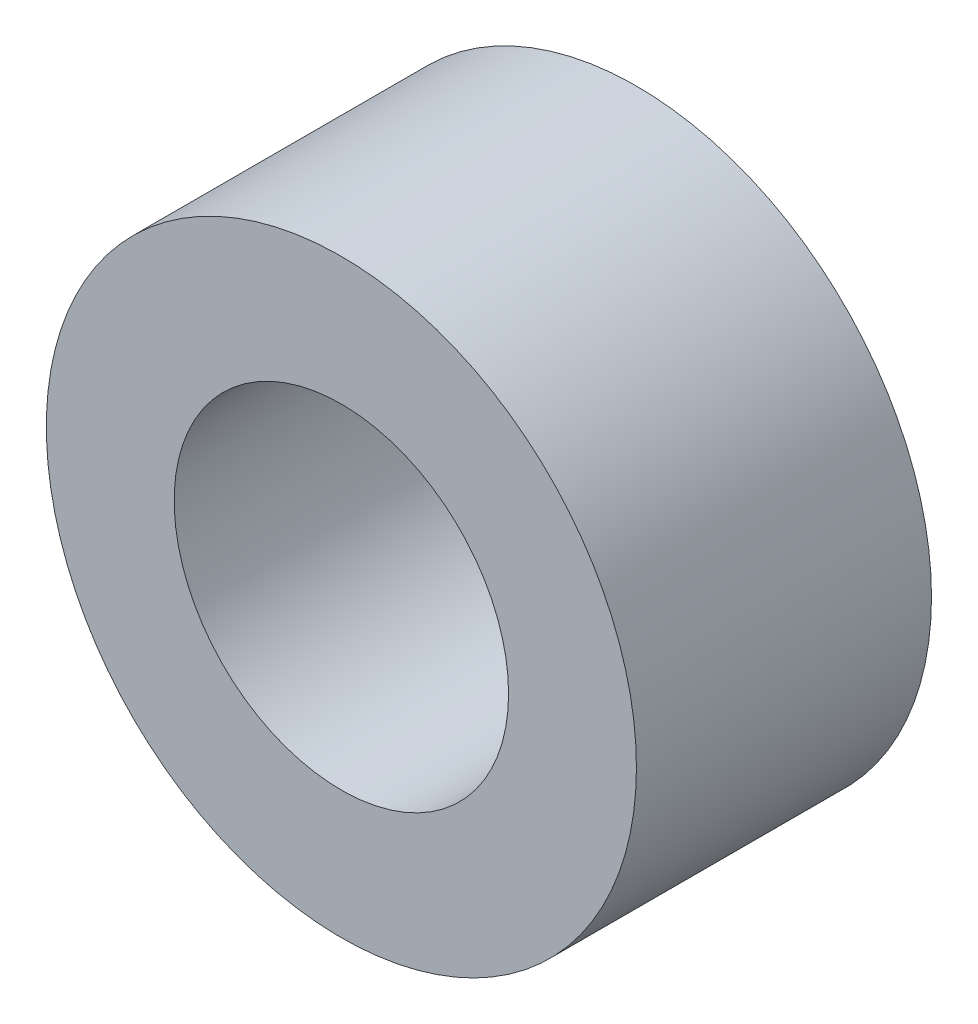
SolidWorks part; units mm, degrees
other "Wheel PWM Board PCA9685 Mount 1 Standoff"
ref_plane "Front Plane" through (0, 0, 0) normal (0, 0, 1) x (1, 0, 0)
ref_plane "Top Plane" through (0, 0, 0) normal (0, 1, 0) x (1, 0, 0)
ref_plane "Right Plane" through (0, 0, 0) normal (1, 0, 0) x (0, 0, -1)
sketch3d "Main Profile Sketch datum points"
  point P0 (0, 0, 51.5)
  point P1 (10, 0, 51.5)
  point P2 (0, 10, 51.5)
ref_plane "Main Profile Sketch plane" through (0, 0, 51.5) normal (0, 0, 1) x (1, 0, 0)
sketch "Main Profile Sketch" plane through (0, 0, 51.5) normal (0, 0, 1) x (1, 0, 0)
  circle A0 centre (-151.5, -27) radius 3
  circle A1 centre (-151.5, -27) radius 1.7
extrude "Main Extrusion" add sketch "Main Profile Sketch" against normal blind 3 separate body
